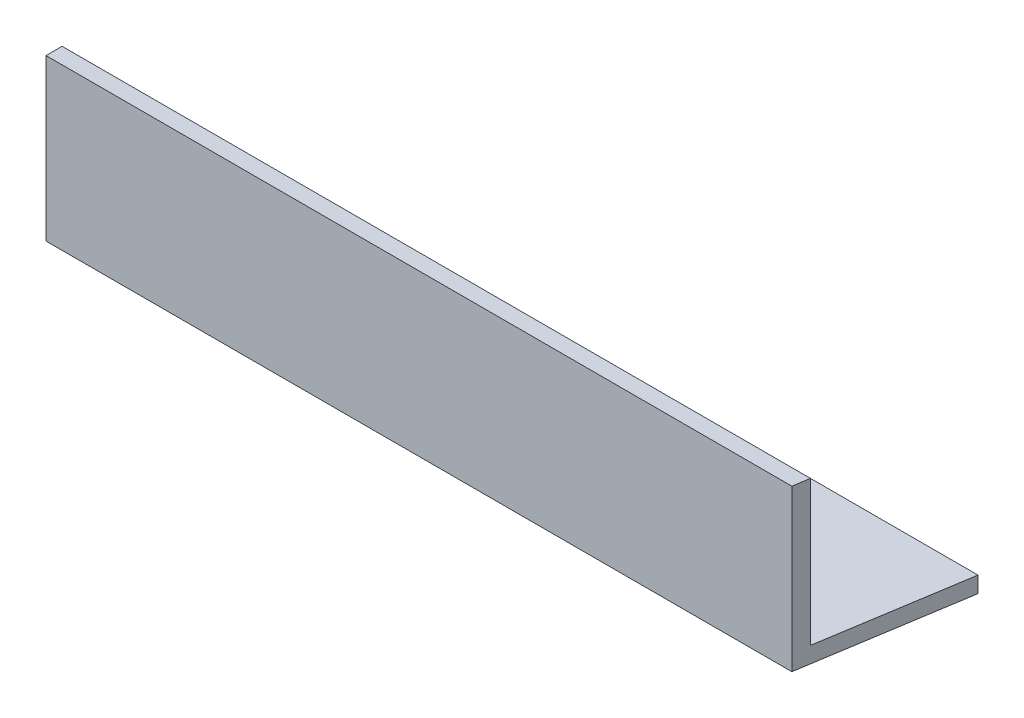
SolidWorks part; units mm, degrees
ref_plane "Front Plane" through (0, 0, 0) normal (0, 0, 1) x (1, 0, 0)
ref_plane "Top Plane" through (0, 0, 0) normal (0, 1, 0) x (1, 0, 0)
ref_plane "Right Plane" through (0, 0, 0) normal (1, 0, 0) x (0, 0, -1)
sketch "Sketch1" plane through (0, 0, 0) normal (1, 0, 0) x (0, 0, -1)
  line L0 (0, 20) -> (0, 0)
  line L1 (0, 0) -> (20, 0)
  line L2 (20, 0) -> (20, 2)
  line L3 (20, 2) -> (2, 2)
  line L4 (2, 2) -> (2, 20)
  line L5 (0, 20) -> (2, 20)
  dimension "D1" = 20
  dimension "D2" = 20
  dimension "D3" = 2
  dimension "D4" = 2
extrude "Boss-Extrude1" add sketch "Sketch1" along normal blind 96
sketch "Sketch2" plane through (0, 0, 0) normal (0, 1, 0) x (1, 0, 0)
  line L11 (96, 20) -> (92.8323, 0)
  line L12 (96, 0) -> (0, 0) construction
  line L13 (92.8323, 0) -> (96, 0)
  line L14 (96, 0) -> (96, 20)
  dimension "D1" = 9
extrude "Cut-Extrude1" cut sketch "Sketch2" along normal through all
